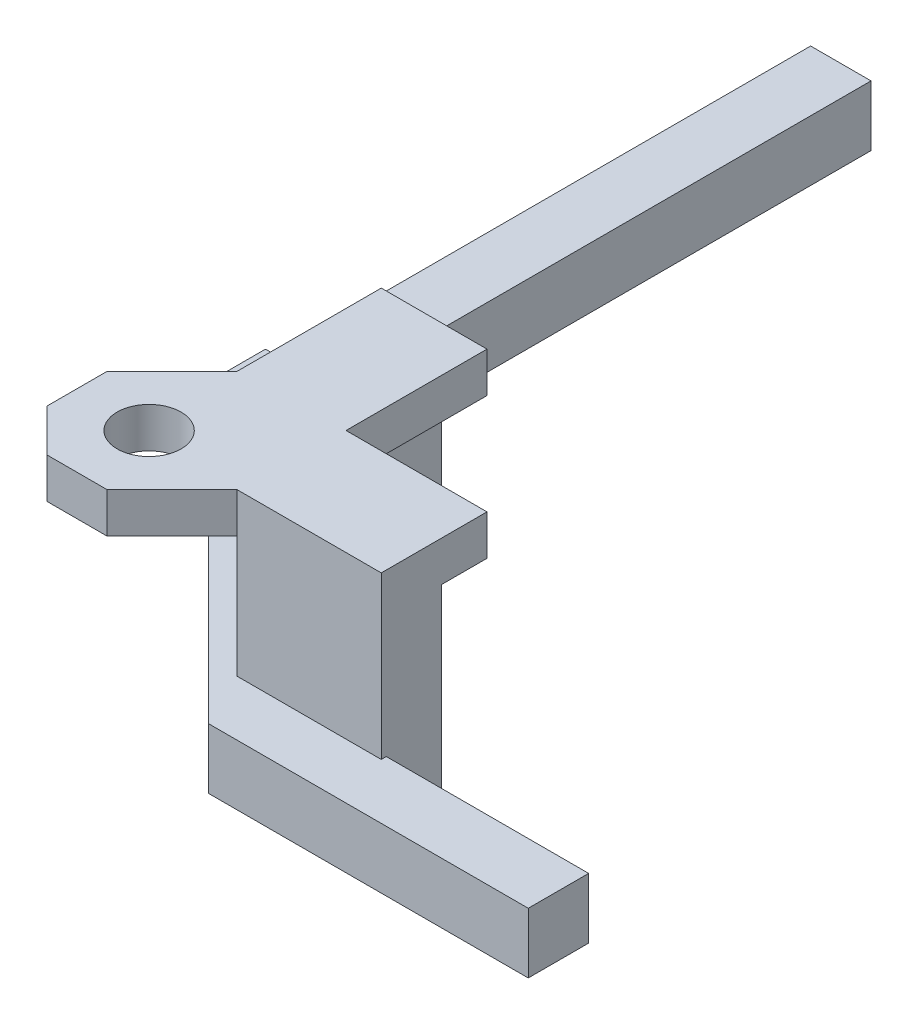
SolidWorks part; units mm, degrees
ref_plane "Front Plane" through (0, 0, 0) normal (0, 0, 1) x (1, 0, 0)
ref_plane "Top Plane" through (0, 0, 0) normal (0, 1, 0) x (1, 0, 0)
ref_plane "Right Plane" through (0, 0, 0) normal (1, 0, 0) x (0, 0, -1)
sketch "Sketch1" plane through (0, 0, 0) normal (0, 1, 0) x (1, 0, 0)
  line L0 (-54.15, 0) -> (-60.15, 0)
  line L1 (-60.15, 0) -> (-60.15, -53.15)
  line L2 (-60.15, -53.15) -> (-61.15, -53.15)
  line L3 (-61.15, -53.15) -> (-61.15, -61.15)
  line L4 (-61.15, -61.15) -> (-58.8069, -61.15)
  line L6 (-58.8069, -61.15) -> (-31.7569, -88.2)
  line L17 (-54.15, 0) -> (-54.15, -53.15)
  line L18 (-54.15, -53.15) -> (-53.15, -53.15)
  line L19 (-53.15, -53.15) -> (-53.15, -58.2)
  line L24 (-54.15, 0) -> (0, 0) construction
  line L25 (0, 0) -> (0, -92.25) construction
  line L26 (-38.6, -58.2) -> (-38.1, -58.2) construction
  line L27 (-38.1, 0) -> (-38.1, -76.2) construction
  line L28 (-61.15, -57.15) -> (-53.15, -57.15) construction
  line L29 (-38.1, -76.2) -> (0, -76.2) construction
  line L37 (-38.1, -76.2) -> (-38.6, -76.7) construction
  line L38 (-38.6, -76.7) -> (-38.6, -58.2) construction
  line L39 (-53.15, -58.2) -> (-38.6, -58.2)
  line L41 (-38.6, -76.7) -> (-20.1, -76.7) construction
  line L42 (-20.1, -76.7) -> (-20.1, -82.2)
  line L44 (-31.7569, -88.2) -> (0, -88.2)
  line L45 (0, -88.2) -> (0, -82.2)
  line L46 (0, -82.2) -> (-20.1, -82.2)
  line L47 (-38.6, -58.2) -> (-38.6, -70.0431)
  line L49 (-31.9431, -76.7) -> (-20.1, -76.7)
  line L50 (-20.1, -76.7) -> (-20.1, -76.2) construction
  line L51 (-38.6, -70.0431) -> (-31.9431, -76.7)
  point P8 (-56.6502, -61.15)
  point P16 (-30.8461, -88.2)
  point P23 (-57.785, -61.3817)
  point P37 (-57.15, 0)
  dimension "D1" = 6
  dimension "D2" = 8
  dimension "D4" = 57.15
  dimension "D5" = 57.15
  dimension "D6" = 76.2
  dimension "D7" = 38.1
  dimension "D8" = 45
  dimension "D10" = 6
  dimension "D9" = 18
  dimension "D3" = 0.5
  dimension "D11" = 135
  dimension "D12" = 4
  dimension "D13" = 4
extrude "Boss-Extrude1" add sketch "Sketch1" along normal blind 6
sketch "Sketch2" plane through (0, 0, 0) normal (0, -1, 0) x (1, 0, 0)
  line L0 (-53.15, 58.2) -> (-53.15, 53.15) construction
  line L1 (-61.15, 53.15) -> (-61.15, 61.15) construction
  line L2 (-53.15, 58.2) -> (-53.15, 53.15)
  line L3 (-61.15, 53.15) -> (-61.15, 61.15)
  line L5 (-61.15, 53.15) -> (-53.15, 53.15)
  line L6 (-61.15, 61.15) -> (-53.15, 61.15)
  line L7 (-53.15, 61.15) -> (-53.15, 58.2)
extrude "Boss-Extrude2" add sketch "Sketch2" along normal blind 1
sketch "Sketch3" plane through (0, 6, 0) normal (0, 1, 0) x (1, 0, 0)
  line L4 (-38.6, -58.2) -> (-44.6, -58.2)
  line L6 (-44.6, -58.2) -> (-44.6, -72.5284)
  line L9 (-20.1, -82.7) -> (-20.1, -76.7)
  line L10 (-44.6, -72.5284) -> (-34.4284, -82.7)
  line L11 (-34.4284, -82.7) -> (-20.1, -82.7)
  line L12 (-58.8069, -61.15) -> (-31.7569, -88.2) construction
  line L13 (-38.6, -58.2) -> (-38.6, -70.0431)
  line L14 (-38.6, -70.0431) -> (-31.9431, -76.7)
  line L15 (-31.9431, -76.7) -> (-20.1, -76.7)
  line L16 (-20.1, -76.7) -> (-31.9431, -76.7) construction
  line L17 (-38.6, -70.0431) -> (-38.6, -58.2) construction
  line L18 (-38.6, -58.2) -> (-53.15, -58.2) construction
  line L19 (-20.1, -82.2) -> (-20.1, -76.7) construction
  line L20 (-38.6, -70.0431) -> (-42.8426, -74.2858) construction
  line L21 (-38.6, -70.0431) -> (-44.6, -70.0431) construction
  point P6 (-46.1805, -69.5431)
  point P22 (-35.1917, -86.2498)
  dimension "D1" = 6
extrude "Boss-Extrude3" add sketch "Sketch3" along normal blind 12.05
sketch "Sketch4" plane through (0, 18.05, 0) normal (0, 1, 0) x (1, 0, 0)
  line L0 (-44.6, -58.2) -> (-34.1, -58.2)
  line L1 (-34.1, -58.2) -> (-34.1, -72.2)
  line L2 (-34.1, -72.2) -> (-20.1, -72.2)
  line L3 (-20.1, -72.2) -> (-20.1, -82.7)
  line L4 (-20.1, -82.7) -> (-34.453, -82.7)
  line L5 (-34.4284, -82.7) -> (-20.1, -82.7) construction
  line L6 (-34.453, -82.7) -> (-40.9086, -89.1556)
  line L7 (-40.9086, -89.1556) -> (-46.8526, -89.1556)
  line L8 (-46.8526, -89.1556) -> (-51.0556, -84.9526)
  line L9 (-51.0556, -84.9526) -> (-51.0556, -79.0086)
  line L10 (-51.0556, -79.0086) -> (-44.6, -72.553)
  line L11 (-44.6, -72.553) -> (-44.6, -58.2)
  line L12 (-43.8806, -81.9806) -> (-48.9541, -87.0541) construction
  line L13 (-43.8806, -81.9806) -> (-51.0556, -81.9806) construction
  line L14 (-41.6355, -79.7355) -> (-39.5142, -77.6142) construction
  line L15 (-44.6, -72.5284) -> (-34.4284, -82.7) construction
  circle A0 centre (-43.8806, -81.9806) radius 3.175
  point P3 (-42.7453, -80.8453)
  point P16 (0, 0)
  dimension "D4" = 6.35
  dimension "D1" = 10.5
  dimension "D2" = 135
  dimension "D3" = 135
  dimension "D5" = 7.175
extrude "Boss-Extrude4" add sketch "Sketch4" along normal blind 4
sketch "Sketch5" plane through (-58.5642, 0, 58.5642) normal (-0.7071, 0, 0.7071) x (0.7071, 0, 0.7071)
  line L0 (19.7484, 18.05) -> (19.7484, 6) construction
  line L1 (19.7484, 18.05) -> (34.1332, 18.05)
  line L2 (19.7484, 18.05) -> (19.7484, 10.05)
  line L3 (19.7484, 10.05) -> (34.1332, 10.05)
  line L4 (34.1332, 18.05) -> (34.1332, 10.05)
  line L5 (34.1332, 18.05) -> (34.1332, 6) construction
  line L6 (19.7484, 18.05) -> (34.1332, 18.05) construction
  dimension "D1" = 8
extrude "Cut-Extrude1" cut sketch "Sketch5" against normal up to next and the other way through all
equation "\"sample_clearance\"= 0.5'sample to edge wall"
equation "\"truss_width\"= 6'thickness"
equation "\"truss_height\"= 6'thickness"
equation "\"truss_offset\"= 1'height offset from baseplate"
equation "\"D1@Sketch1\"=\"truss_width\""
equation "\"screw_spacing_short\"= 4.5in'baseplate spacing parallel to sample short side"
equation "\"screw_spacing_long\"= 4.5in'baseplate spacing parallel to sample long side"
equation "\"truss_bore_width\"= 8'box around bore hole"
equation "\"D2@Sketch1\"=\"truss_bore_width\""
equation "\"D4@Sketch1\"=\"screw_spacing_long\"/2"
equation "\"D5@Sketch1\"=\"screw_spacing_short\"/2"
equation "\"sample_long\"= 6in"
equation "\"sample_short\"= 3in"
equation "\"D6@Sketch1\"=\"sample_long\"/2"
equation "\"D7@Sketch1\"=\"sample_short\"/2"
equation "\"base_clearance_corner\" = 2"
equation "\"wall\" = 12"
equation "\"sample_short_to_truss\"= 6"
equation "\"D10@Sketch1\"=\"sample_short_to_truss\""
equation "\"D1@Boss-Extrude1\"=\"truss_height\""
equation "\"D1@Boss-Extrude2\"=\"truss_offset\""
equation "\"D1@Boss-Extrude3\"=0.75in - \"truss_offset\" - \"truss_height\""
equation "\"D3@Sketch1\"=\"sample_clearance\""
equation "\"D1@Sketch4\"=\"sample_clearance\"+10"
